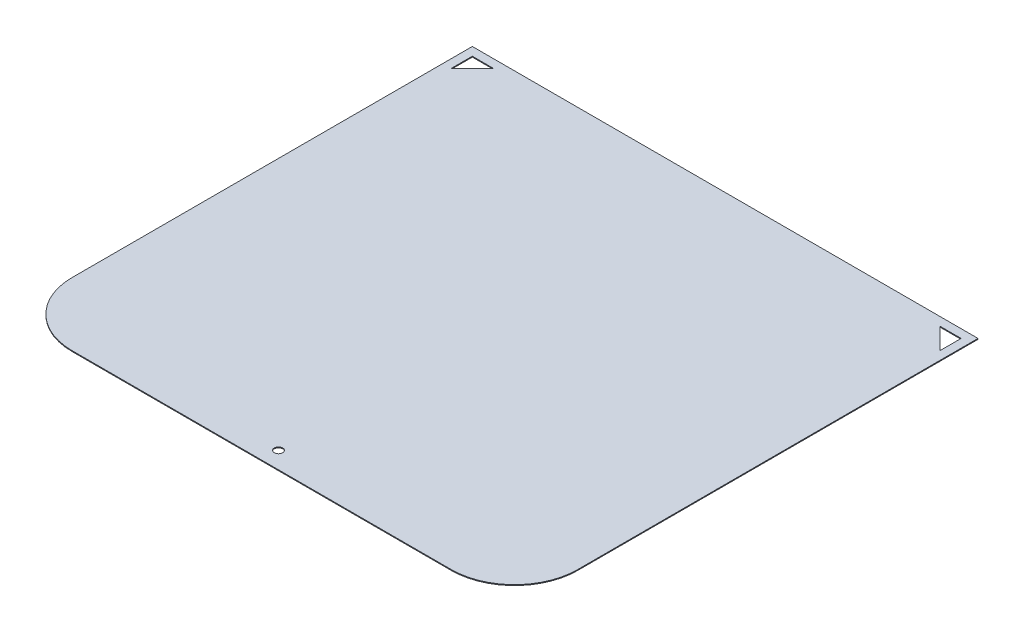
SolidWorks part; units mm, degrees
ref_plane "前视基准面" through (0, 0, 0) normal (0, 0, 1) x (1, 0, 0)
ref_plane "上视基准面" through (0, 0, 0) normal (0, 1, 0) x (1, 0, 0)
ref_plane "右视基准面" through (0, 0, 0) normal (1, 0, 0) x (0, 0, -1)
sketch "Sketch1" plane through (0, 0, 0) normal (0, 1, 0) x (1, 0, 0)
  line L1 (0, 0) -> (120, 0)
  line L2 (0, 0) -> (0, 110)
  line L3 (0, 110) -> (120, 110)
  line L4 (120, 0) -> (120, 110)
  dimension "D1" = 110
  dimension "D2" = 120
extrude "Boss-Extrude1" add sketch "Sketch1" along normal blind 0.2
fillet "Fillet1" radius 15 2 edges at (0, 0.1, 0) (120, 0.1, 0)
sketch "Sketch2" plane through (0, 0.2, 0) normal (0, 1, 0) x (1, 0, 0)
  line L0 (60, 100) -> (60, 50) construction
  line L1 (2, 108) -> (7, 108)
  line L2 (7, 108) -> (2, 103)
  line L3 (2, 103) -> (2, 108)
  line L4 (120, 110) -> (0, 110) construction
  line L5 (60, 0) -> (60, 4) construction
  line L6 (0, 110) -> (0, 15) construction
  line L7 (118, 103) -> (118, 108)
  line L8 (113, 108) -> (118, 103)
  line L9 (118, 108) -> (113, 108)
  line L10 (15, 0) -> (105, 0) construction
  circle A4 centre (60, 4) radius 1
  dimension "D1" = 2
  dimension "D2" = 2
  dimension "D3" = 5
extrude "Cut-Extrude1" cut sketch "Sketch2" against normal blind 5
